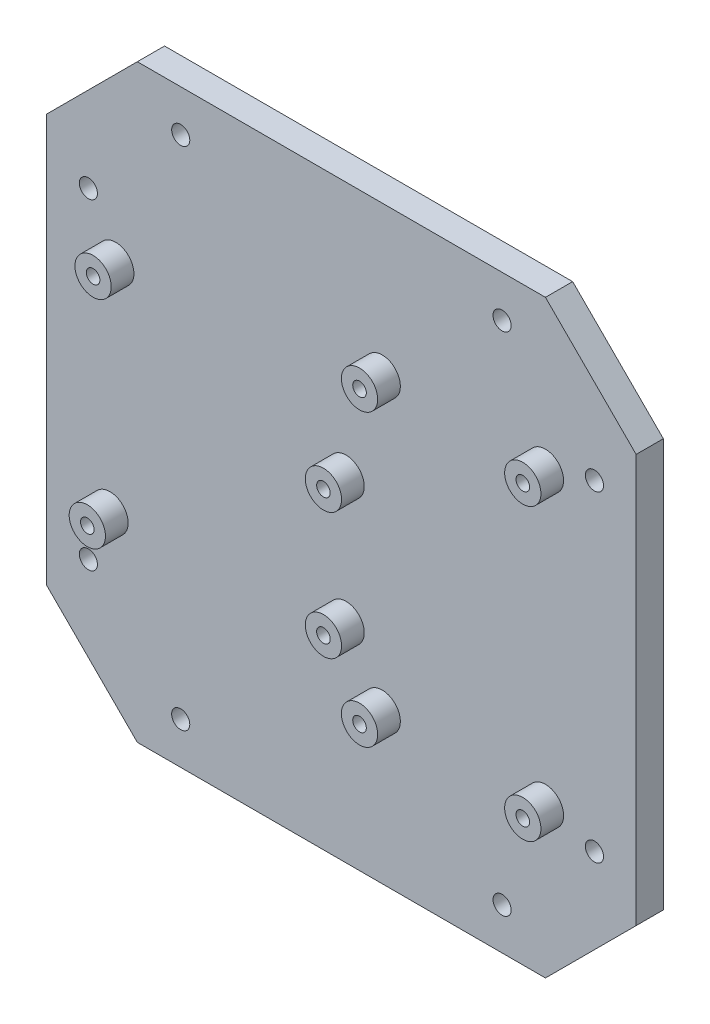
SolidWorks part; units mm, degrees
ref_plane "前基準面" through (0, 0, 0) normal (0, 0, 1) x (1, 0, 0)
ref_plane "上基準面" through (0, 0, 0) normal (0, 1, 0) x (1, 0, 0)
ref_plane "右基準面" through (0, 0, 0) normal (1, 0, 0) x (0, 0, -1)
sketch "草圖1" plane through (0, 0, 0) normal (0, 0, 1) x (1, 0, 0)
  line L2 (0, 0) -> (0, 130)
  line L4 (-130, 0) -> (-130, 130)
  line L5 (-130, 130) -> (0, 130)
  line L37 (-130, 0) -> (0, 0)
  dimension "D2" = 130
  dimension "D3" = 130
extrude "填料-伸長1" add sketch "草圖1" along normal blind 6
ref_plane "平面1" through (0, 0, -35.9) normal (0, 0, 1) x (1, 0, 0)
sketch "草圖10" plane through (0, 0, 6) normal (0, 0, 1) x (1, 0, 0)
  line L1 (-130, 130) -> (-130, 0) construction
  line L2 (-130, 0) -> (0, 0) construction
  circle A0 centre (-114.76, 89.13) radius 1.5
  circle A1 centre (-63.96, 73.89) radius 1.5
  circle A2 centre (-63.96, 45.95) radius 1.5
  circle A3 centre (-116.03, 40.87) radius 1.5
  dimension "D4" = 50.8
  dimension "D6" = 3
  dimension "D7" = 5.08
  dimension "D8" = 40.87
  dimension "D9" = 50.8
  dimension "D2" = 48.26
  dimension "D3" = 27.94
  dimension "D5" = 1.27
  dimension "D1" = 15.24
extrude "除料-伸長1" cut sketch "草圖10" against normal up to surface (6 mm away) up to face at (-65, 65, 0)
sketch "草圖11" plane through (0, 0, 6) normal (0, 0, 1) x (1, 0, 0)
  line L0 (-29.5647, 120.8) -> (-29.5647, 130) construction
  line L1 (0, 130) -> (-130, 130) construction
  line L2 (-65, 130) -> (-65, 0) construction
  line L3 (-130, 0) -> (0, 0) construction
  line L4 (-120.8, 100.4353) -> (-130, 100.4353) construction
  line L5 (-9.1975, 102.4353) -> (-9.2, 100.4353) construction
  line L6 (-9.2, 100.4353) -> (0, 100.4353) construction
  line L7 (0, 0) -> (0, 130) construction
  line L8 (-130, 130) -> (-130, 0) construction
  line L9 (-130, 65) -> (0, 65) construction
  line L10 (-120.8025, 102.4353) -> (-120.8, 100.4353) construction
  line L11 (-100.4353, 120.8) -> (-100.4353, 130) construction
  line L12 (-100.4353, 9.2) -> (-100.4353, 0) construction
  line L13 (-120.8025, 27.5647) -> (-120.8, 29.5647) construction
  line L14 (-9.2, 29.5647) -> (0, 29.5647) construction
  line L15 (-9.1975, 27.5647) -> (-9.2, 29.5647) construction
  line L16 (-120.8, 29.5647) -> (-130, 29.5647) construction
  line L17 (-29.5647, 9.2) -> (-29.5647, 0) construction
  line L18 (-29.5647, 120.8) -> (-9.2, 100.4353) construction
  circle A0 centre (-9.2, 100.4353) radius 2
  circle A1 centre (-29.5647, 120.8) radius 2
  circle A2 centre (-100.4353, 120.8) radius 2
  circle A3 centre (-120.8, 100.4353) radius 2
  circle A4 centre (-120.8, 29.5647) radius 2
  circle A5 centre (-100.4353, 9.2) radius 2
  circle A6 centre (-29.5647, 9.2) radius 2
  circle A7 centre (-9.2, 29.5647) radius 2
  dimension "D1" = 9.2
  dimension "D2" = 135
  dimension "D4" = 28.8
  dimension "D6" = 4
  dimension "D8" = 4
extrude "除料-伸長2" cut sketch "草圖11" against normal up to next
chamfer "導角1" distance 20 angle 45 4 edges at (0, 130, 3) (0, 0, 3) (-130, 0, 3) (-130, 130, 3)
sketch "草圖12" plane through (0, 0, 6) normal (0, 0, 1) x (1, 0, 0)
  line L0 (-56, 97) -> (-56, 33) construction
  line L1 (-56, 33) -> (-20, 33) construction
  line L2 (-20, 33) -> (-20, 97) construction
  line L3 (-20, 97) -> (-56, 97) construction
  line L4 (0, 20) -> (0, 110) construction
  circle A0 centre (-56, 97) radius 1.5
  circle A1 centre (-20, 97) radius 1.5
  circle A2 centre (-56, 33) radius 1.5
  circle A3 centre (-20, 33) radius 1.5
  point P7 (-20, 65)
  point P9 (0, 65)
  dimension "D1" = 64
  dimension "D2" = 36
  dimension "D3" = 3
  dimension "D4" = 20
  dimension "D5" = 0
extrude "除料-伸長3" cut sketch "草圖12" against normal up to next
sketch "草圖13" plane through (0, 0, 6) normal (0, 0, 1) x (1, 0, 0)
  circle A0 centre (-114.76, 89.13) radius 1.5
  circle A1 centre (-114.76, 89.13) radius 4
  circle A2 centre (-56, 97) radius 1.5
  circle A3 centre (-56, 97) radius 4
  circle A4 centre (-116.03, 40.87) radius 4
  circle A5 centre (-116.03, 40.87) radius 1.5
  circle A6 centre (-63.96, 73.89) radius 4
  circle A7 centre (-63.96, 73.89) radius 1.5
  circle A8 centre (-63.96, 45.95) radius 4
  circle A9 centre (-63.96, 45.95) radius 1.5
  circle A10 centre (-56, 33) radius 4
  circle A11 centre (-56, 33) radius 1.5
  circle A12 centre (-20, 33) radius 4
  circle A13 centre (-20, 33) radius 1.5
  circle A14 centre (-20, 97) radius 4
  circle A15 centre (-20, 97) radius 1.5
  dimension "D1" = 8
  dimension "D2" = 3
extrude "填料-伸長2" add sketch "草圖13" along normal blind 5
